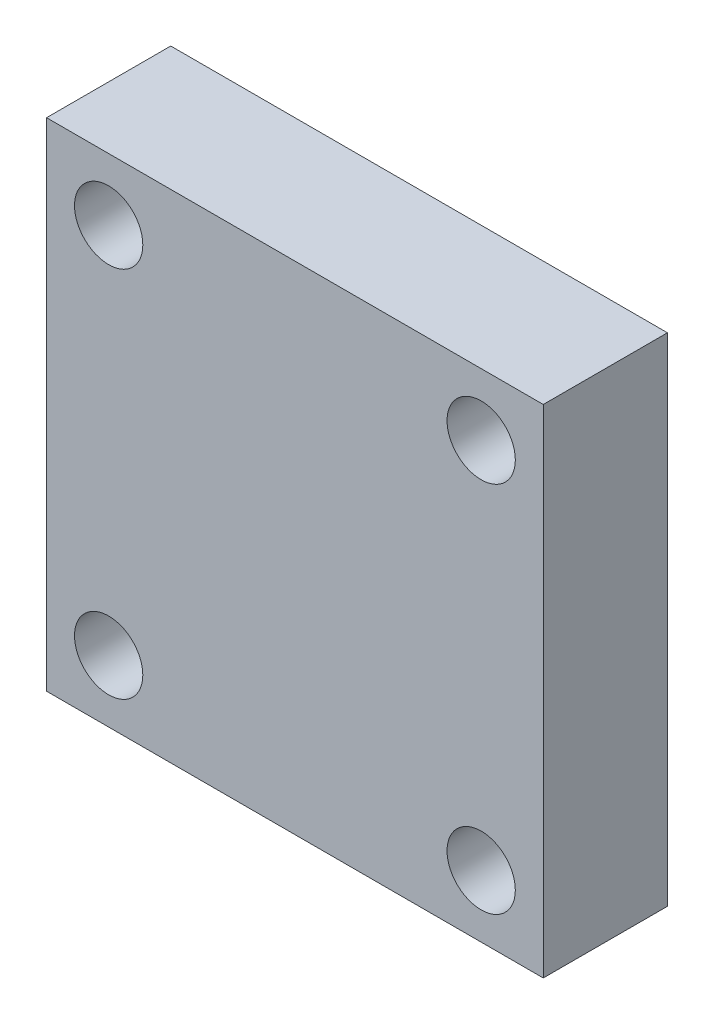
SolidWorks part; units mm, degrees
ref_plane "Спереди" through (0, 0, 0) normal (0, 0, 1) x (1, 0, 0)
ref_plane "Сверху" through (0, 0, 0) normal (0, 1, 0) x (1, 0, 0)
ref_plane "Справа" through (0, 0, 0) normal (1, 0, 0) x (0, 0, -1)
sketch "Эскиз1" plane through (0, 0, 0) normal (0, 0, 1) x (1, 0, 0)
  line L1 (-20, -20) -> (20, -20)
  line L2 (-20, -20) -> (-20, 20)
  line L3 (-20, 20) -> (20, 20)
  line L4 (20, -20) -> (20, 20)
  line L5 (-20, -20) -> (20, 20) construction
  line L6 (-20, 20) -> (20, -20) construction
  circle A0 centre (-15, -15) radius 2.75
  circle A1 centre (15, -15) radius 2.75
  circle A2 centre (15, 15) radius 2.75
  circle A3 centre (-15, 15) radius 2.75
  point P0 (0, 0)
  point P14 (0, 0)
  point P15 (0, 0)
  point P16 (0, 0)
  dimension "D2" = 5.5
  dimension "D1" = 40
  dimension "D3" = 30
extrude "Бобышка-Вытянуть1" add sketch "Эскиз1" along normal blind 10
